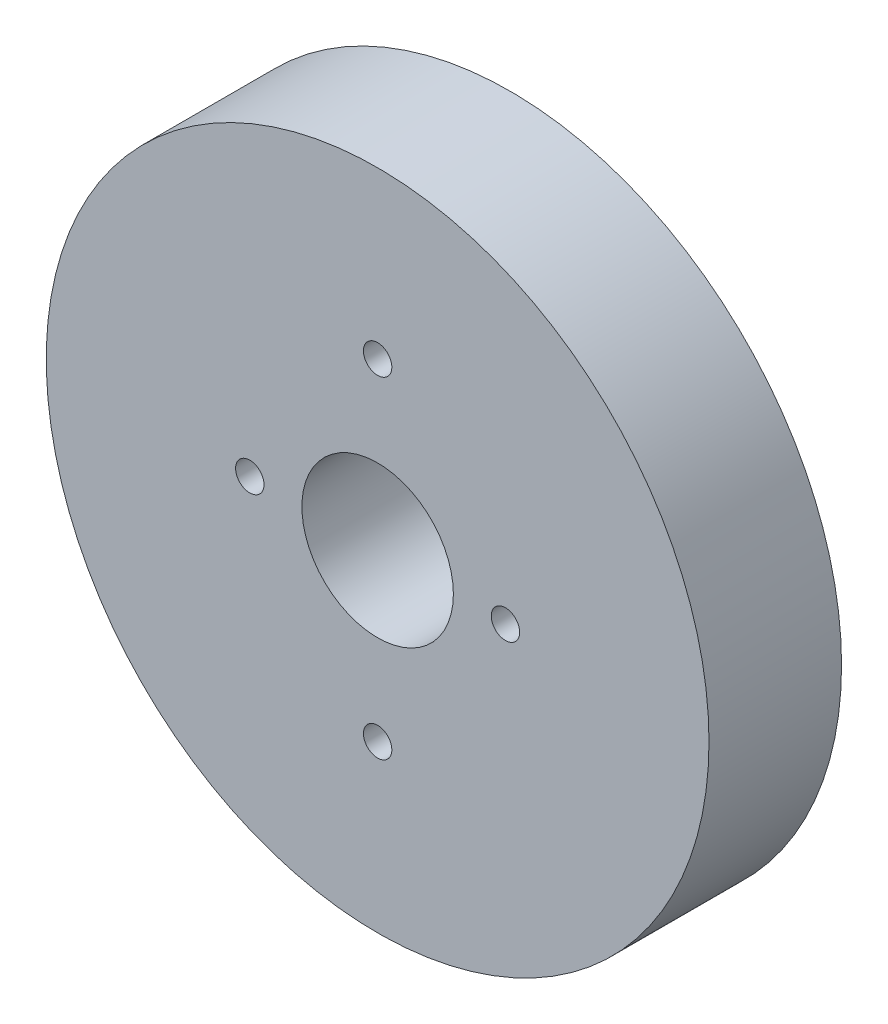
SolidWorks part; units mm, degrees
ref_plane "前视基准面" through (0, 0, 0) normal (0, 0, 1) x (1, 0, 0)
ref_plane "上视基准面" through (0, 0, 0) normal (0, 1, 0) x (1, 0, 0)
ref_plane "右视基准面" through (0, 0, 0) normal (1, 0, 0) x (0, 0, -1)
sketch "草图1" plane through (0, 0, 0) normal (0, 0, 1) x (1, 0, 0)
  line L0 (0, 0) -> (24.8546, 0) construction
  line L1 (0, 0) -> (0, 8.75) construction
  circle A0 centre (0, 0) radius 17.5
  circle A1 centre (0, 0) radius 4
  circle A2 centre (6.75, 0) radius 0.75
  circle A3 centre (0, 8.75) radius 0.75
  circle A4 centre (-6.75, 0) radius 0.75
  circle A5 centre (0, -8.75) radius 0.75
  dimension "D1" = 8
  dimension "D2" = 35
  dimension "D3" = 1.5
  dimension "D4" = 6.75
  dimension "D5" = 8.75
extrude "凸台-拉伸1" add sketch "草图1" along normal blind 7
